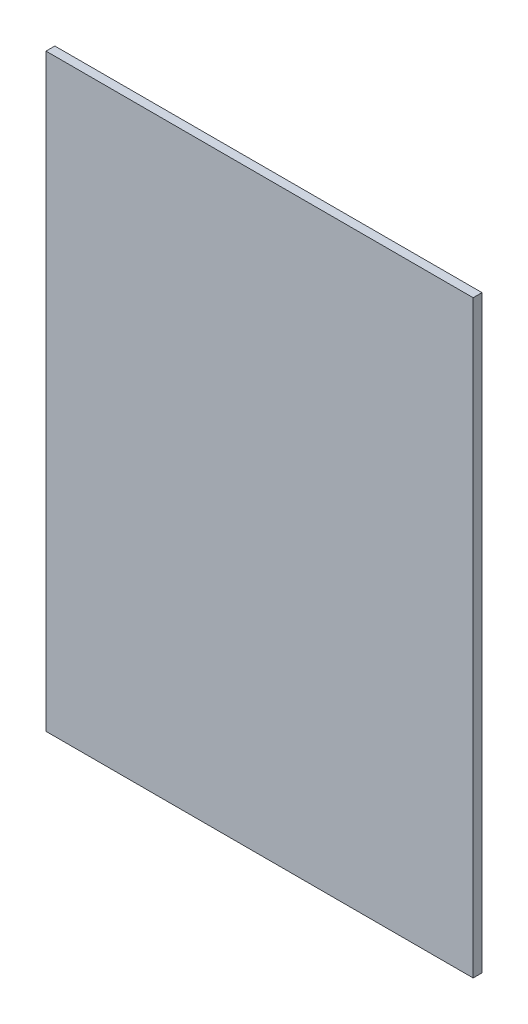
SolidWorks part; units mm, degrees
ref_plane "Plano frontal" through (0, 0, 0) normal (0, 0, 1) x (1, 0, 0)
ref_plane "Plano superior" through (0, 0, 0) normal (0, 1, 0) x (1, 0, 0)
ref_plane "Plano direito" through (0, 0, 0) normal (1, 0, 0) x (0, 0, -1)
sketch "Esboço1" plane through (0, 0, 0) normal (0, 0, 1) x (1, 0, 0)
  line L1 (-72.5, -100) -> (72.5, -100)
  line L2 (-72.5, -100) -> (-72.5, 100)
  line L3 (-72.5, 100) -> (72.5, 100)
  line L4 (72.5, -100) -> (72.5, 100)
  line L5 (-72.5, -100) -> (72.5, 100) construction
  line L6 (-72.5, 100) -> (72.5, -100) construction
  point P0 (0, 0)
  dimension "D1" = 200
  dimension "D2" = 145
extrude "Ressalto-extrusão1" add sketch "Esboço1" along normal blind 3
